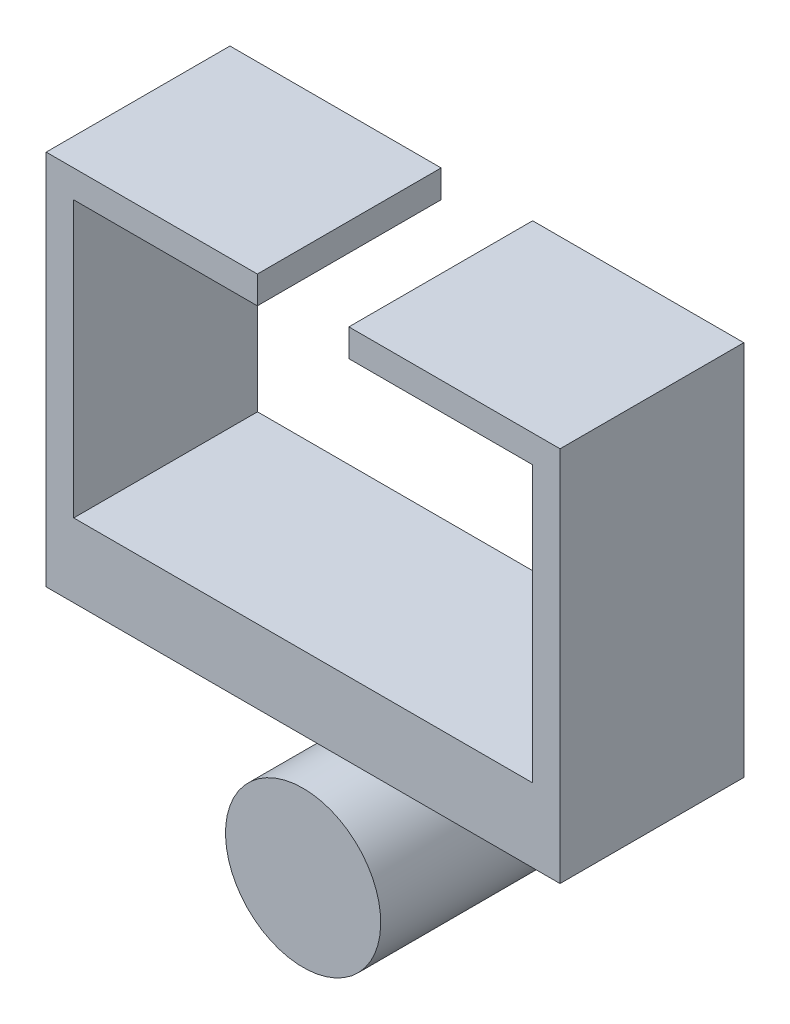
SolidWorks part; units mm, degrees
material "6061-T6 (SS)"
ref_plane "Front Plane" through (0, 0, 0) normal (0, 0, 1) x (1, 0, 0)
ref_plane "Top Plane" through (0, 0, 0) normal (0, 1, 0) x (1, 0, 0)
ref_plane "Right Plane" through (0, 0, 0) normal (1, 0, 0) x (0, 0, -1)
sketch "Sketch1" plane through (0, 0, 0) normal (0, 0, 1) x (1, 0, 0)
  line L0 (-35.5117, 17.0688) -> (35.5117, 17.0688)
  line L1 (35.5117, 17.0688) -> (35.5117, 69.1134)
  line L2 (35.5117, 69.1134) -> (6.3246, 69.1134)
  line L3 (6.3246, 69.1134) -> (6.3246, 65.3034)
  line L4 (6.3246, 65.3034) -> (31.7043, 65.3034)
  line L5 (31.7043, 65.3034) -> (31.7043, 27.2288)
  line L6 (31.7043, 27.2288) -> (-31.7043, 27.2288)
  line L7 (-31.7043, 27.2288) -> (-31.7043, 65.3034)
  line L8 (-31.7043, 65.3034) -> (-6.3246, 65.3034)
  line L9 (-6.3246, 65.3034) -> (-6.3246, 69.1134)
  line L10 (-6.3246, 69.1134) -> (-35.5117, 69.1134)
  line L11 (-35.5117, 69.1134) -> (-35.5117, 17.0688)
  line L12 (0, 0) -> (0, 17.0688) construction
  circle A0 centre (0, 0) radius 10.7287
  dimension "D1" = 21.4574
  dimension "D5" = 38.0746
  dimension "D6" = 71.0235
  dimension "D7" = 3.8075
  dimension "D8" = 3.81
  dimension "D11" = 10.16
  dimension "D12" = 17.0688
  dimension "D2" = 63.4086
  dimension "D3" = 29.1871
extrude "Boss-Extrude1" add sketch "Sketch1" along normal blind 25.4
sketch "Sketch2" plane through (0, 17.0688, 0) normal (0, -1, 0) x (1, 0, 0)
  line L0 (-10.7287, 25.4) -> (-10.7287, 0) construction
  line L1 (-10.7287, 0) -> (10.7287, 0)
  line L2 (-10.7287, 0) -> (-10.7287, 6.35)
  line L3 (-10.7287, 6.35) -> (10.7287, 6.35)
  line L4 (10.7287, 0) -> (10.7287, 6.35)
  line L5 (10.7287, 0) -> (10.7287, 25.4) construction
  line L6 (-10.7287, 0) -> (10.7287, 0) construction
  dimension "D1" = 6.35
extrude "Boss-Extrude2" add sketch "Sketch2" along normal blind 17.0688
sketch "Sketch3" plane through (0, 0, 0) normal (1, 0, 0) x (0, 0, -1)
  line L0 (-25.4, 10.7287) -> (-6.35, 10.7287)
  line L3 (-6.35, 10.7287) -> (-25.4, 10.7287) construction
split line "Split Line1"
equation "\"SF\"= 4"
equation "\"YieldS\"= 40000"
equation "\"E\"= 10 ^ 6"
equation "\"b\"= 1"
equation "\"F\"= 500"
equation "\"La\"= 1"
equation "\"Za\"= \"F\" * \"SF\" * \"La\" * 2 / ( \"YieldS\" * 2 )"
equation "\"Defl\"= 0.005"
equation "\"Da\"= ( ( 16 * \"F\" * \"La\" ) / ( \"E\" * \"Defl\" * pi ) ) ^ ( 1 / 4 )"
equation "\"Lb\"= .672"
equation "\"bb\"= \"Da\""
equation "\"hb\"= ( 2 * \"F\" * \"Lb\" ) / ( \"bb\" * \"E\" * \"Defl\" )"
equation "\"Lc\"= 2.4964"
equation "\"hc\"= ( ( 24 * \"F\" * ( \"Lc\" ^ 3 ) ) / ( 48 * \"E\" * \"b\" * \"Defl\" ) ) ^ ( 1 / 3 )"
equation "\"Ld\"= 1.499"
equation "\"hd\"= ( \"F\" * \"Ld\" ) / ( \"E\" * \"b\" * \"Defl\" )"
equation "\"Le\"= 0.9992"
equation "\"he\"= ( ( \"SF\" * \"F\" * \"Le\" * 3 ) / ( \"YieldS\" * \"b\" ) ) ^ ( 1 / 2 )"
equation "\"D1@Sketch1\"=\"Da\""
equation "\"D12@Sketch1\"=\"Lb\""
equation "\"D11@Sketch1\"=.4"
equation "\"D5@Sketch1\"=\"Ld\""
equation "\"D8@Sketch1\"=.15"
equation "\"D7@Sketch1\"=\"hd\""
equation "\"D1@Sketch2\"=.25"
equation "\"D2@Sketch1\"=\"Lc\""
equation "\"bottomL\"= \"Lc\" + 2 * \"hd\""
equation "\"D6@Sketch1\"=\"bottomL\""
